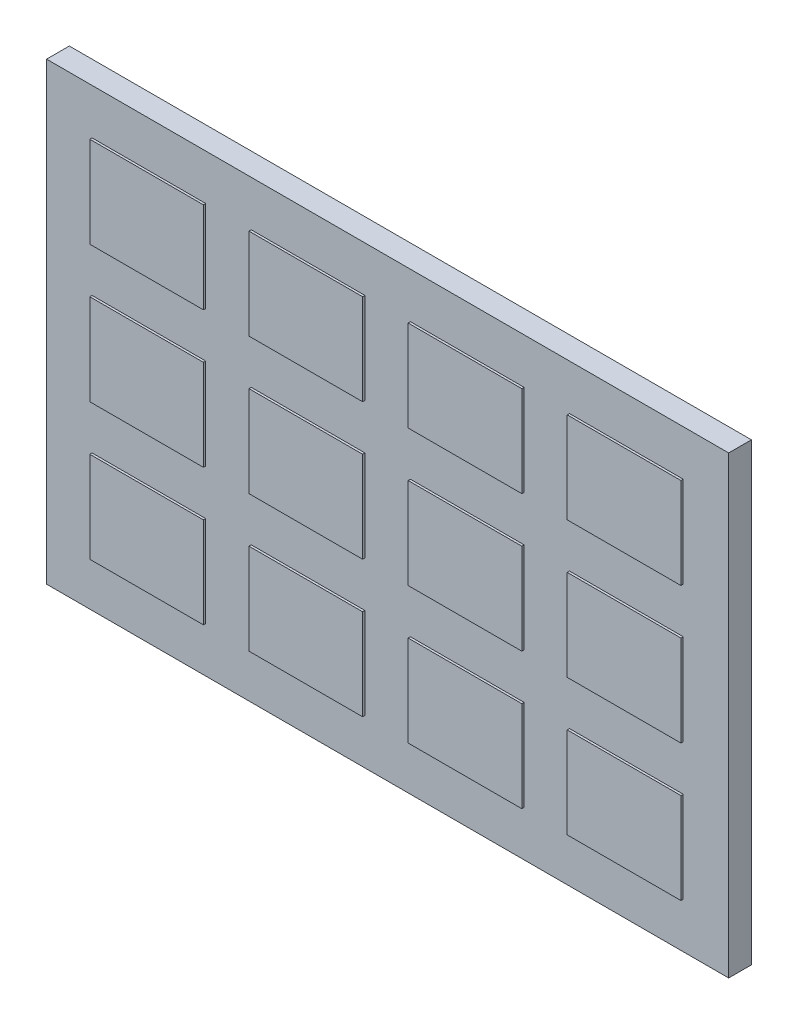
SolidWorks part; units mm, degrees
ref_plane "Front Plane" through (0, 0, 0) normal (0, 0, 1) x (1, 0, 0)
ref_plane "Top Plane" through (0, 0, 0) normal (0, 1, 0) x (1, 0, 0)
ref_plane "Right Plane" through (0, 0, 0) normal (1, 0, 0) x (0, 0, -1)
sketch "Sketch1" plane through (0, 0, 0) normal (0, 0, 1) x (1, 0, 0)
  line L1 (38.1, -25.4) -> (-38.1, -25.4)
  line L2 (38.1, -25.4) -> (38.1, 25.4)
  line L3 (38.1, 25.4) -> (-38.1, 25.4)
  line L4 (-38.1, -25.4) -> (-38.1, 25.4)
  line L5 (38.1, -25.4) -> (-38.1, 25.4) construction
  line L6 (38.1, 25.4) -> (-38.1, -25.4) construction
  point P0 (0, 0)
  dimension "D1" = 50.8
  dimension "D2" = 76.2
extrude "Boss-Extrude2" add sketch "Sketch1" along normal blind 2.54
sketch "Sketch3" plane through (0, 0, 2.54) normal (0, 0, 1) x (1, 0, 0)
  line L0 (-38.1, 25.4) -> (-38.1, -25.4) construction
  line L1 (-33.02, 20.32) -> (-20.32, 20.32)
  line L2 (-33.02, 20.32) -> (-33.02, 10.16)
  line L3 (-33.02, 10.16) -> (-20.32, 10.16)
  line L4 (-20.32, 20.32) -> (-20.32, 10.16)
  line L5 (38.1, 25.4) -> (-38.1, 25.4) construction
  dimension "D1" = 12.7
  dimension "D2" = 10.16
  dimension "D3" = 5.08
  dimension "D4" = 5.08
extrude "Boss-Extrude3" add sketch "Sketch3" along normal blind 0.254
pattern_linear "LPattern2" count 4 spacing 17.78 along (1, 0, 0) count 3 spacing 15.24 along (0, -1, 0) of "Boss-Extrude3"
